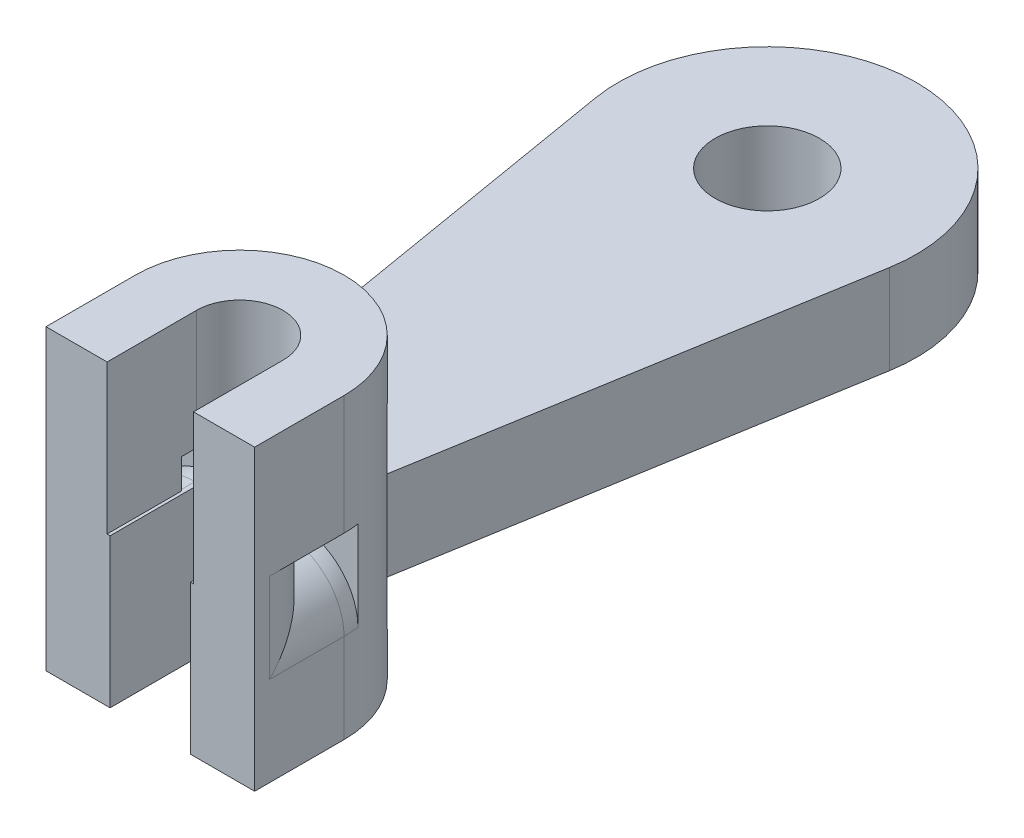
SolidWorks part; units mm, degrees
ref_plane "Front Plane" through (0, 0, 0) normal (0, 0, 1) x (1, 0, 0)
ref_plane "Top Plane" through (0, 0, 0) normal (0, 1, 0) x (1, 0, 0)
ref_plane "Right Plane" through (0, 0, 0) normal (1, 0, 0) x (0, 0, -1)
sketch "Sketch1" plane through (0, 0, 0) normal (0, 1, 0) x (1, 0, 0)
  line L0 (-1.35, 0) -> (-1.35, -3)
  line L1 (1.35, 0) -> (1.35, -3)
  line L2 (-3.5, 0) -> (-3.5, -3)
  line L3 (3.5, 0) -> (3.5, -3)
  line L4 (3.5, -3) -> (1.35, -3)
  line L5 (-1.35, -3) -> (-3.5, -3)
  arc A0 (1.35, 0) -> (-1.35, 0) centre (0, 0) ccw
  arc A1 (3.5, 0) -> (-3.5, 0) centre (0, 0) ccw
  dimension "D1" = 2.7
  dimension "D2" = 7
  dimension "D3" = 3
extrude "Boss-Extrude1" add sketch "Sketch1" along normal blind 5
sketch "Sketch2" plane through (0, 5, 0) normal (0, 1, 0) x (1, 0, 0)
  line L0 (-1.45, -2.9) -> (-1.45, 0)
  line L1 (1.45, 0) -> (1.45, -2.9)
  line L6 (1.35, 0) -> (1.35, -3)
  line L7 (1.35, -3) -> (3.5, -3)
  line L8 (3.5, -3) -> (3.5, 0)
  line L9 (-3.5, 0) -> (-3.5, -3)
  line L10 (-3.5, -3) -> (-1.35, -3)
  line L11 (-1.35, -3) -> (-1.35, 0)
  line L13 (1.45, -3) -> (3.5, -3)
  line L14 (3.5, -3) -> (3.5, 0)
  line L15 (-3.5, 0) -> (-3.5, -3)
  line L16 (-3.5, -3) -> (-1.45, -3)
  line L18 (-1.45, -2.9) -> (-1.45, -3)
  line L19 (1.45, -2.9) -> (1.45, -3)
  line L20 (1.35, -3) -> (3.5, -3) construction
  line L21 (-3.4, -2.9) -> (-1.45, -2.9) construction
  line L22 (-3.4, 0) -> (-3.4, -2.9) construction
  line L23 (1.45, -2.9) -> (3.4, -2.9) construction
  line L24 (3.4, -2.9) -> (3.4, 0) construction
  line L25 (1.35, 0) -> (1.35, -3) construction
  line L26 (-1.35, -3) -> (-1.35, 0) construction
  line L27 (-3.5, -3) -> (-1.35, -3) construction
  arc A0 (1.45, 0) -> (-1.45, 0) centre (0, 0) ccw
  arc A2 (1.35, 0) -> (-1.35, 0) centre (0, 0) ccw
  arc A3 (3.5, 0) -> (-3.5, 0) centre (0, 0) ccw
  arc A5 (3.5, 0) -> (-3.5, 0) centre (0, 0) ccw
  arc A6 (3.4, 0) -> (-3.4, 0) centre (0, 0) ccw construction
  arc A7 (1.35, 0) -> (-1.35, 0) centre (0, 0) ccw construction
  dimension "D1" = 0
  dimension "D2" = 0.1
extrude "Boss-Extrude2" add sketch "Sketch2" along normal blind 5
sketch "Sketch3" plane through (-1.45, 0, 0) normal (1, 0, 0) x (0, 0, -1)
  line L0 (-3, 5) -> (0, 5) construction
  line L1 (-0.5, 5) -> (0.5, 5)
  line L2 (-0.5, 5) -> (-0.5, 6)
  line L3 (-0.5, 6) -> (0.5, 6)
  line L4 (0.5, 5) -> (0.5, 6)
  line L5 (0, 10) -> (0, 5) construction
  point P6 (0, 5)
  dimension "D1" = 1
  dimension "D2" = 1
extrude "Cut-Extrude1" cut sketch "Sketch3" against normal through all both and the other way through all
fillet "Fillet1" radius 2 6 edges at (3.5, 5.5, 0.5) (-3.5, 5.5, 0.5) (3.5, 5, 0.25) (3.491, 5, -0.2506) (-3.491, 5, -0.2506) (-3.5, 5, 0.25)
sketch "Sketch4" plane through (0, 6, 0) normal (0, -1, 0) x (1, 0, 0)
  line L0 (0, -17.7) -> (0, 0) construction
  line L1 (-4.9305, -16.869) -> (-2.5, -2.4495)
  line L2 (2.5, -2.4495) -> (4.9305, -16.869)
  circle A0 centre (0, -17.7) radius 1.75
  arc A1 (-4.9305, -16.869) -> (4.9305, -16.869) centre (0, -17.7) ccw
  arc A2 (-2.5, -2.4495) -> (2.5, -2.4495) centre (0, 0) ccw
  arc A3 (-3.5, 0) -> (3.5, 0) centre (0, 0) ccw construction
  point P7 (-4.843, -16.4569)
  point P10 (5, -1.513)
  point P11 (2.5436, -2.4042)
  point P15 (-2.1971, -2.4042)
  point P16 (0, 0)
  point P17 (5, -17.7)
  point P18 (4.843, -16.4569)
  point P19 (2.2965, -2.6412)
  point P20 (1.9608, -2.8992)
  point P21 (-2.2437, -2.6862)
  point P22 (0, 0)
  dimension "D1" = 3.5
  dimension "D3" = 10
  dimension "D2" = 17.7
  dimension "D4" = 5
extrude "Boss-Extrude3" add sketch "Sketch4" along normal blind 3
